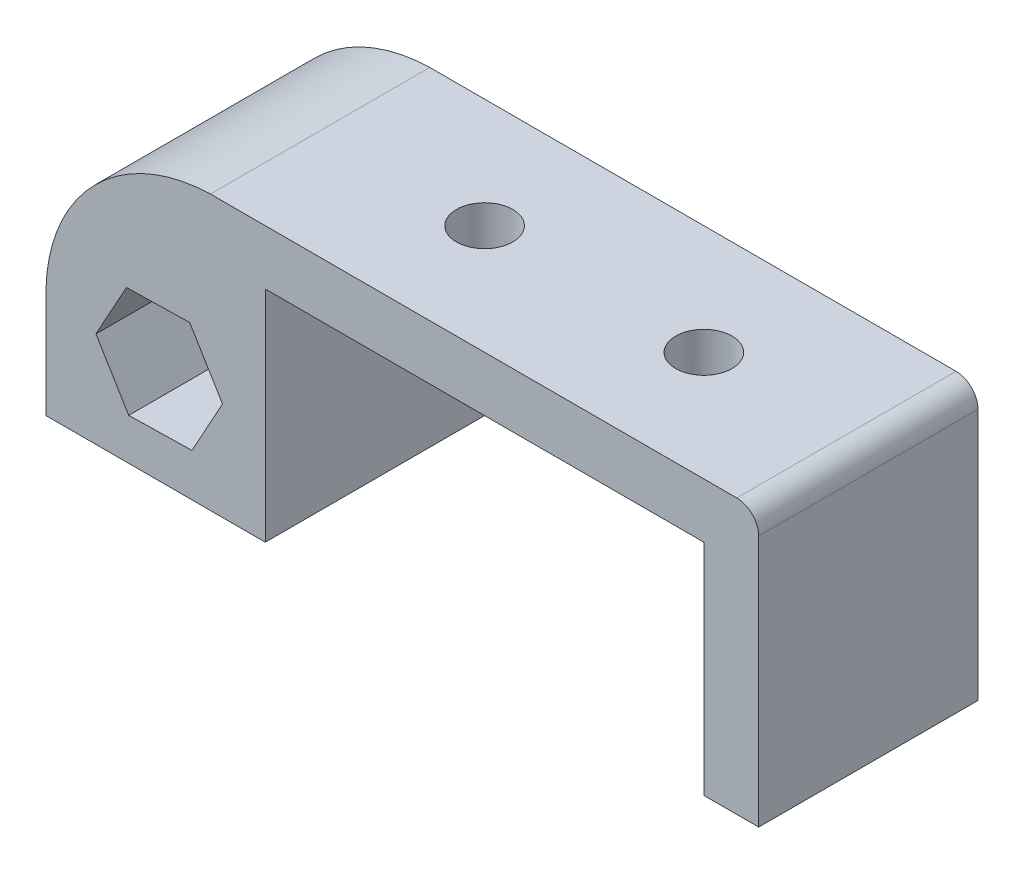
SolidWorks part; units mm, degrees
material "Printed PLA Orthotropic"
ref_plane "Front Plane" through (0, 0, 0) normal (0, 0, 1) x (1, 0, 0)
ref_plane "Top Plane" through (0, 0, 0) normal (0, 1, 0) x (1, 0, 0)
ref_plane "Right Plane" through (0, 0, 0) normal (1, 0, 0) x (0, 0, -1)
sketch "Sketch1" plane through (0, 0, 0) normal (0, 0, 1) x (1, 0, 0)
  line L0 (50.8, 0) -> (57.15, 0)
  line L2 (0, 0) -> (0, 25.4)
  line L3 (0, 25.4) -> (50.8, 25.4)
  line L4 (50.8, 0) -> (50.8, 25.4)
  line L5 (57.15, 0) -> (57.15, 29.21)
  line L6 (54.61, 31.75) -> (-6.35, 31.75)
  line L7 (0, 0) -> (-25.4, 0)
  line L8 (-8.4894, 4.9677) -> (-4.9553, 11.3921)
  line L9 (-4.9553, 11.3921) -> (-8.752, 17.6649)
  line L10 (-8.752, 17.6649) -> (-16.0828, 17.5133)
  line L11 (-16.0828, 17.5133) -> (-19.6169, 11.0888)
  line L12 (-19.6169, 11.0888) -> (-15.8202, 4.816)
  line L13 (-15.8202, 4.816) -> (-8.4894, 4.9677)
  line L14 (-25.4, 0) -> (-25.4, 12.7)
  arc A0 (57.15, 29.21) -> (54.61, 31.75) centre (54.61, 29.21) ccw
  circle A1 centre (-12.2861, 11.2405) radius 6.35 construction
  arc A2 (-25.4, 12.7) -> (-6.35, 31.75) centre (-5.849, 12.199) cw
  point P10 (57.15, 31.75)
  dimension "D6" = 2.54
  dimension "D8" = 12.7
  dimension "D1" = 50.8
  dimension "D2" = 25.4
  dimension "D3" = 63.5
  dimension "D4" = 31.75
  dimension "D5" = 6.35
  dimension "D7" = 12.7
  dimension "D9" = 25.4
extrude "Boss-Extrude2" add sketch "Sketch1" along normal blind 25.4
sketch "Sketch2" plane through (0, 31.75, 0) normal (0, 1, 0) x (1, 0, 0)
  line L0 (54.61, 0) -> (-6.35, 0) construction
  line L1 (25.4, 0) -> (25.4, -25.4) construction
  circle A0 centre (12.7, -12.7) radius 3.2639
  circle A1 centre (38.1, -12.7) radius 3.2639
  point P4 (0, 0)
  point P12 (0, 0)
  point P13 (0, 0)
  dimension "D1" = 12.7
  dimension "D3" = 6.5278
  dimension "D2" = 12.7
  dimension "D4" = 12.7
extrude "Cut-Extrude1" cut sketch "Sketch2" against normal through all
equation "\"x\"=0.1"
